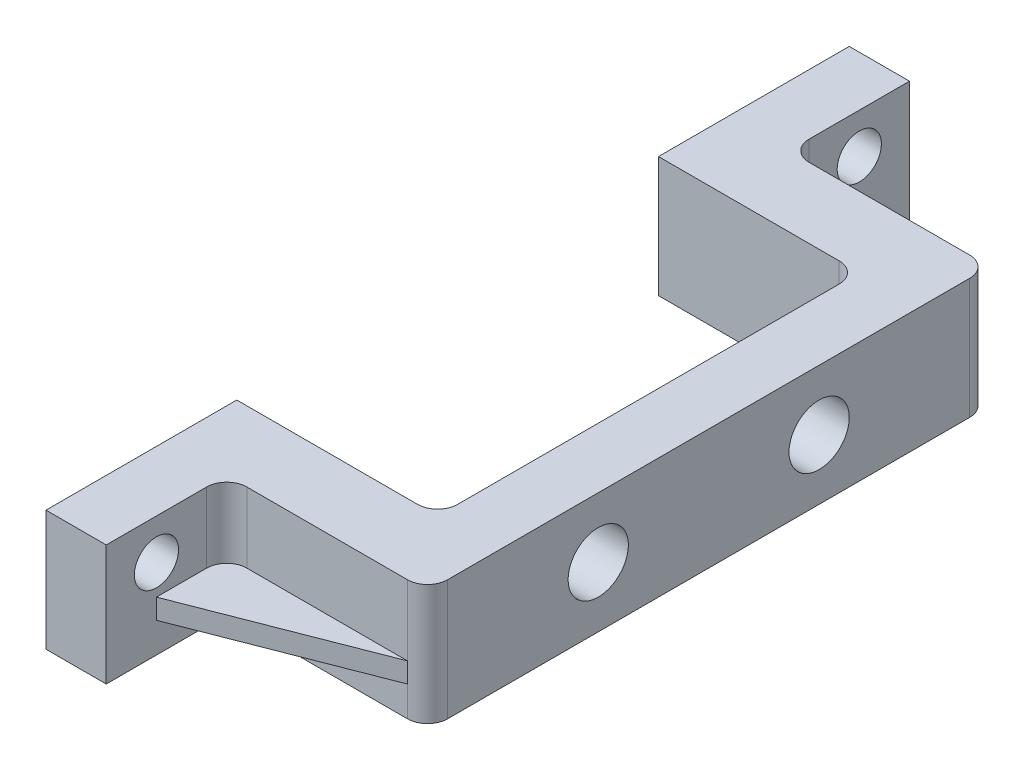
SolidWorks part; units mm, degrees
ref_plane "Front Plane" through (0, 0, 0) normal (1, 0, 0) x (0, 1, 0)
ref_plane "Top Plane" through (0, 0, 0) normal (0, 0, 1) x (0, 1, 0)
ref_plane "Right Plane" through (0, 0, 0) normal (0, 1, 0) x (-1, 0, 0)
sketch "Sketch1" plane through (0, 0, 0) normal (1, 0, 0) x (0, 1, 0)
  line L1 (230.5, -22.5556) -> (236.5, -22.5556)
  line L2 (230.5, -22.5556) -> (230.5, -13.0556)
  line L3 (230.5, 17.4444) -> (236.5, 17.4444)
  line L4 (236.5, -22.5556) -> (236.5, -13.0556)
  line L7 (230.5, -13.0556) -> (236.5, -13.0556)
  line L8 (230.5, 7.9444) -> (236.5, 7.9444)
  line L9 (230.5, 7.9444) -> (230.5, 17.4444)
  line L10 (236.5, 7.9444) -> (236.5, 17.4444)
  line L12 (184, -22.5556) -> (246, -22.5556) construction
  line L13 (184, 17.4444) -> (201, 17.4444) construction
  line L15 (250, -18.5556) -> (250, 13.4444) construction
  dimension "D1" = 6
  dimension "D2" = 19.5
  dimension "D3" = 9.5
  dimension "D4" = 9.5
extrude "Boss-Extrude1" add sketch "Sketch1" along normal blind 10
sketch "Sketch2" plane through (10, 0, 0) normal (1, 0, 0) x (0, 0, -1)
  line L0 (-7.9444, 236.5) -> (-17.4444, 236.5) construction
  line L1 (-17.4444, 230.5) -> (-11.4444, 230.5)
  line L2 (-17.4444, 230.5) -> (-17.4444, 236.5)
  line L3 (-17.4444, 236.5) -> (-11.4444, 236.5)
  line L4 (-11.4444, 230.5) -> (-11.4444, 236.5)
  line L6 (22.5556, 236.5) -> (16.5556, 236.5)
  line L7 (22.5556, 236.5) -> (22.5556, 230.5)
  line L8 (22.5556, 230.5) -> (16.5556, 230.5)
  line L9 (16.5556, 236.5) -> (16.5556, 230.5)
  line L11 (13.0556, 230.5) -> (22.5556, 230.5) construction
  dimension "D1" = 6
extrude "Cut-Extrude1" cut sketch "Sketch2" against normal offset from surface (7 mm away) 3 up to face at (0, 233.5, -17.8056)
sketch "Sketch3" plane through (10, 0, 0) normal (1, 0, 0) x (0, 0, -1)
  line L1 (-11.4444, 230.5) -> (16.5556, 230.5)
  line L2 (-11.4444, 230.5) -> (-11.4444, 236.5)
  line L3 (-11.4444, 236.5) -> (16.5556, 236.5)
  line L4 (16.5556, 230.5) -> (16.5556, 236.5)
extrude "Boss-Extrude2" add sketch "Sketch3" along normal blind 3
sketch "Sketch4" plane through (10, 0, 0) normal (-1, 0, 0) x (0, 0, 1)
  line L1 (-13.0556, 236.5) -> (-13.0556, 230.5) construction
  line L4 (7.9444, 230.5) -> (-13.0556, 230.5) construction
  circle A0 centre (-8.0556, 233.5) radius 1.5
  circle A2 centre (2.9444, 233.5) radius 1.5
  point P2 (0, 0)
  point P11 (-5.5, -18.8515)
  dimension "D1" = 3
  dimension "D2" = 3
  dimension "D3" = 5
  dimension "D4" = 11
extrude "Cut-Extrude2" cut sketch "Sketch4" against normal blind 3
fillet "Fillet1" radius 1 6 edges at (10, 233.5, 7.9444) (10, 233.5, -13.0556) (3, 233.5, 11.4444) (13, 233.5, 11.4444) (13, 233.5, -16.5556) (3, 233.5, -16.5556)
ref_plane "Plane1" through (0, 232.5, 0) normal (0, -1, 0) x (-1, 0, 0)
sketch "Sketch5" plane through (0, 232.5, 0) normal (0, -1, 0) x (-1, 0, 0)
  line L0 (-12, 16.5556) -> (-3, 20.0556)
  line L1 (-3, 17.5556) -> (-3, 22.5556) construction
  line L2 (-3, 20.0556) -> (-3, 16.5556)
  line L3 (-3, 16.5556) -> (-12, 16.5556)
  line L5 (-9, 13.0556) -> (0, 13.0556) construction
  line L7 (0, 0) -> (31.3611, 0) construction
  line L8 (-12, -11.4444) -> (-3, -14.9444)
  line L9 (-3, -14.9444) -> (-3, -11.4444)
  line L10 (-3, -11.4444) -> (-12, -11.4444)
  line L11 (-12, -11.4444) -> (-4, -11.4444) construction
  line L12 (-3, -17.4444) -> (-3, -12.4444) construction
  point P18 (-11.4421, -11.4444)
  point P20 (0, 0)
  point P21 (-3, -16.1291)
extrude "Boss-Extrude3" add sketch "Sketch5" along normal mid plane 1
sketch "Sketch6" plane through (3, 0, 0) normal (1, 0, 0) x (0, 0, -1)
  line L0 (22.5556, 236.5) -> (17.5556, 236.5) construction
  line L1 (22.5556, 230.5) -> (22.5556, 236.5) construction
  line L2 (2.5556, 0) -> (2.5556, -63.913) construction
  circle A0 centre (20.0556, 234.5) radius 1.1
  circle A1 centre (-14.9444, 234.5) radius 1.1
  dimension "D1" = 2.2
  dimension "D2" = 2
  dimension "D3" = 2.5
extrude "Cut-Extrude3" cut sketch "Sketch6" against normal up to surface (3 mm away) up to face at (0, 233.5, 12.6944)
